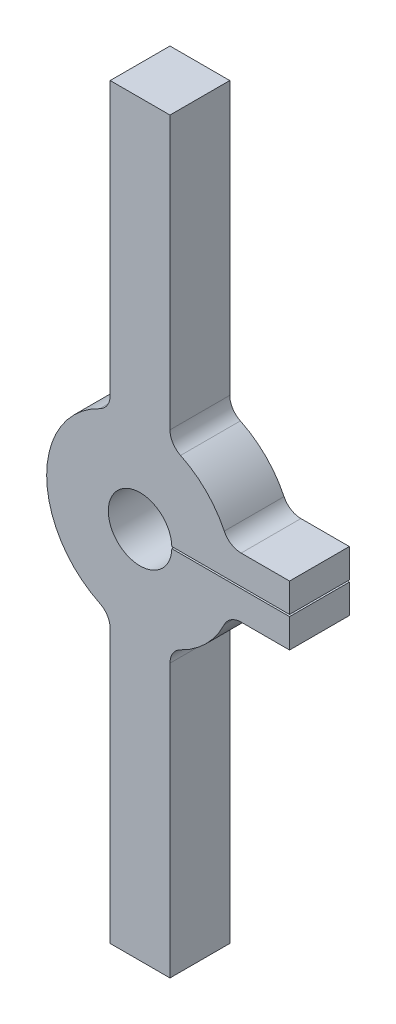
SolidWorks part; units mm, degrees
ref_plane "Front Plane" through (0, 0, 0) normal (0, 0, 1) x (1, 0, 0)
ref_plane "Top Plane" through (0, 0, 0) normal (0, 1, 0) x (1, 0, 0)
ref_plane "Right Plane" through (0, 0, 0) normal (1, 0, 0) x (0, 0, -1)
sketch "Sketch1" plane through (0, 0, 0) normal (0, 0, 1) x (1, 0, 0)
  circle A0 centre (0, 0) radius 8.5
  circle A1 centre (0, 0) radius 25
  dimension "D1" = 17
  dimension "D2" = 50
extrude "Boss-Extrude1" add sketch "Sketch1" along normal mid plane 16
sketch "Sketch2" plane through (0, 0, 0) normal (0, 0, 1) x (1, 0, 0)
  line L0 (0, 0) -> (0, 40.1669) construction
  line L1 (-8, 100) -> (8, 100)
  line L2 (8, 100) -> (8, 23.6854)
  line L3 (8, 23.6854) -> (-8, 23.6854)
  line L4 (-8, 100) -> (-8, 23.6854)
  circle A0 centre (0, 0) radius 25 construction
  point P10 (0, 23.6854)
  point P11 (0, 100)
  dimension "D1" = 16
  dimension "D2" = 100
extrude "Boss-Extrude2" add sketch "Sketch2" along normal mid plane 16
sketch "Sketch3" plane through (0, 0, 0) normal (0, 0, 1) x (1, 0, 0)
  line L0 (0, 0) -> (0, -28.6568) construction
  line L1 (-8, -100) -> (8, -100)
  line L2 (8, -100) -> (8, -23.6854)
  line L3 (8, -23.6854) -> (-8, -23.6854)
  line L4 (-8, -100) -> (-8, -23.6854)
  arc A0 (-8, 23.6854) -> (8, 23.6854) centre (0, 0) ccw construction
  point P11 (0, -23.6854)
  point P12 (0, -100)
  dimension "D1" = 16
  dimension "D2" = 100
extrude "Boss-Extrude3" add sketch "Sketch3" along normal mid plane 16
sketch "Sketch4" plane through (0, 0, 0) normal (0, 0, 1) x (1, 0, 0)
  line L0 (0, 0) -> (85.7397, 0) construction
  line L1 (40, -8) -> (40, 8)
  line L2 (40, 8) -> (23.6854, 8)
  line L3 (23.6854, 8) -> (23.6854, -8)
  line L4 (40, -8) -> (23.6854, -8)
  circle A0 centre (0, 0) radius 25 construction
  point P11 (40, 0)
  point P12 (23.6854, 0)
  dimension "D1" = 16
  dimension "D2" = 40
extrude "Boss-Extrude4" add sketch "Sketch4" along normal mid plane 16
sketch "Sketch5" plane through (0, 0, 0) normal (0, 0, 1) x (1, 0, 0)
  line L0 (0, 0) -> (67.4641, 0) construction
  line L1 (2, -0.25) -> (2, 0.25)
  line L2 (2, 0.25) -> (50, 0.25)
  line L3 (50, 0.25) -> (50, -0.25)
  line L4 (2, -0.25) -> (50, -0.25)
  point P8 (50, 0)
  point P9 (2, 0)
  dimension "D1" = 0.5
  dimension "D2" = 50
  dimension "D3" = 2
extrude "Cut-Extrude1" cut sketch "Sketch5" against normal through all both and the other way through all
fillet "Fillet1" radius 5 6 edges at (-8, -23.6854, 0) (-8, 23.6854, 0) (8, -23.6854, 0) (23.6854, 8, 0) (8, 23.6854, 0) (23.6854, -8, 0)
